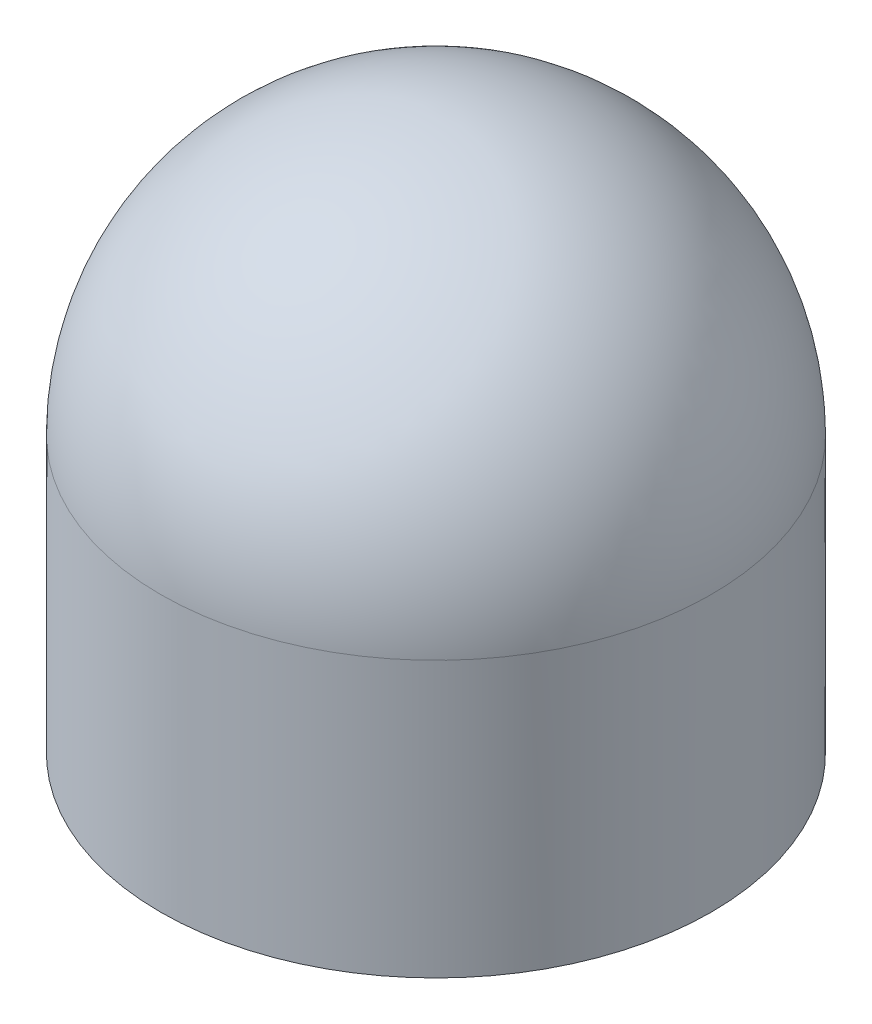
SolidWorks part; units mm, degrees
ref_plane "Front Plane" through (0, 0, 0) normal (0, 0, 1) x (1, 0, 0)
ref_plane "Top Plane" through (0, 0, 0) normal (0, 1, 0) x (1, 0, 0)
ref_plane "Right Plane" through (0, 0, 0) normal (1, 0, 0) x (0, 0, -1)
sketch "Sketch1" plane through (0, 0, 0) normal (0, 1, 0) x (1, 0, 0)
  line L0 (0, 25.4351) -> (0, -25.4351)
  line L1 (0, 25.4351) -> (0, -25.4351) construction
  arc A0 (0, -25.4351) -> (0, 25.4351) centre (0, 0) ccw
revolve "Revolve1" add sketch "Sketch1" angle 180 about L1
sketch "Sketch2" plane through (0, 0, 0) normal (0, -1, 0) x (-1, 0, 0)
  circle A0 centre (0, 0) radius 25.4351
extrude "Boss-Extrude1" add sketch "Sketch2" along normal blind 25.4
